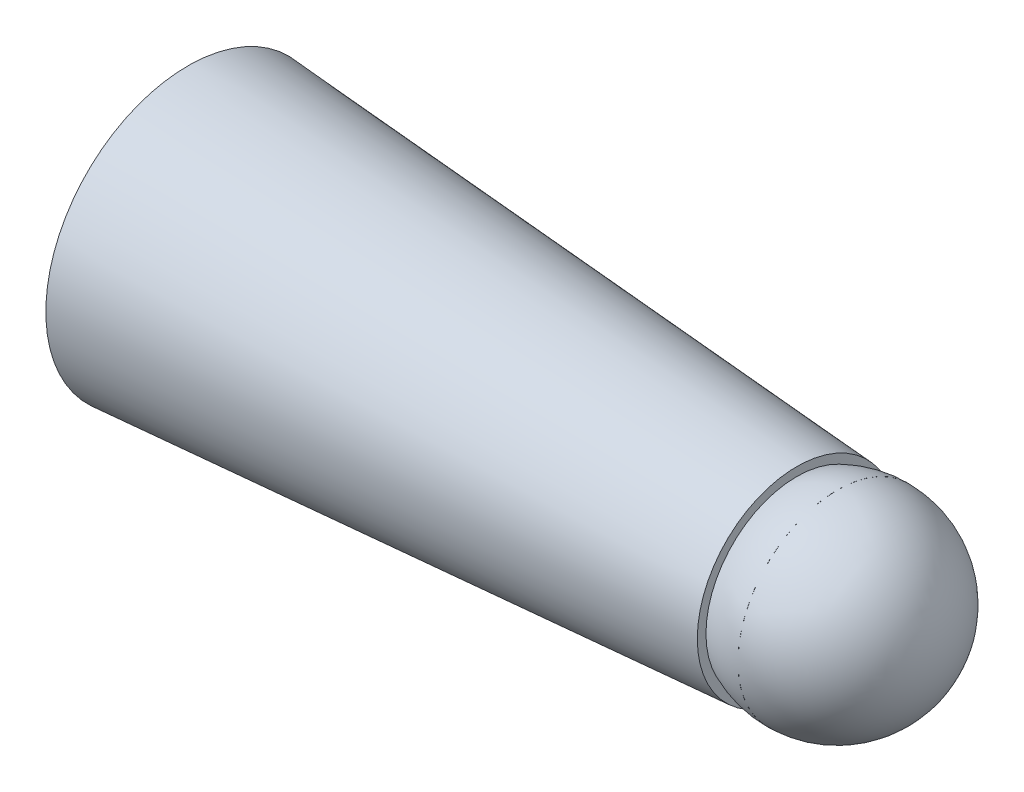
SolidWorks part; units mm, degrees
ref_plane "Front Plane" through (0, 0, 0) normal (0, 0, 1) x (1, 0, 0)
ref_plane "Top Plane" through (0, 0, 0) normal (0, 1, 0) x (1, 0, 0)
ref_plane "Right Plane" through (0, 0, 0) normal (1, 0, 0) x (0, 0, -1)
sketch "Sketch1" plane through (0, 0, 0) normal (1, 0, 0) x (0, 0, -1)
  circle A0 centre (0, 0) radius 3.5
  dimension "D1" = 7
extrude "Boss-Extrude1" add sketch "Sketch1" along normal blind 15 draft 4
surface "Surface-Offset1" parameters "D1"=1
sketch "Sketch2" plane through (16, 0, 0) normal (1, 0, 0) x (0, 0, -1)
  line L0 (0, 2.4511) -> (0, -2.4511) construction
  line L1 (0, 2.4511) -> (0, -2.4511)
  arc A0 (0, -2.4511) -> (0, 2.4511) centre (0, 0) ccw
  circle A1 centre (0, 0) radius 2.4511 construction
  dimension "D1" = 2.4511
revolve "Revolve1" add sketch "Sketch2" angle 360 about L0
